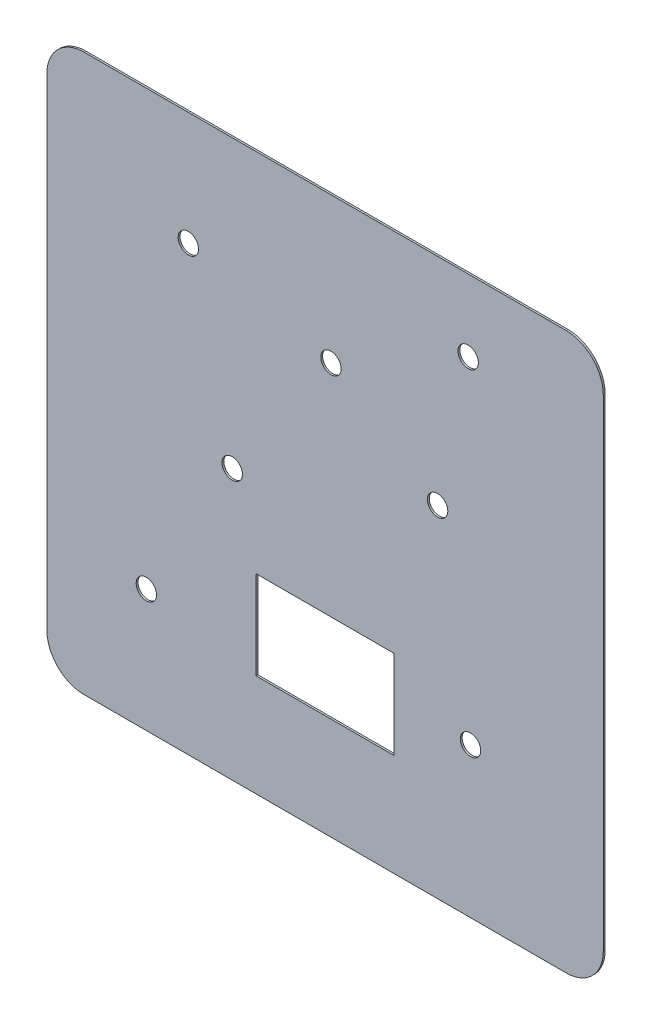
SolidWorks part; units mm, degrees
ref_plane "Piano frontale" through (0, 0, 0) normal (0, 0, 1) x (1, 0, 0)
ref_plane "Piano superiore" through (0, 0, 0) normal (0, 1, 0) x (1, 0, 0)
ref_plane "Piano destro" through (0, 0, 0) normal (1, 0, 0) x (0, 0, -1)
sketch "Schizzo1" plane through (0, 0, 0) normal (0, 0, 1) x (1, 0, 0)
  line L1 (-75, 75) -> (75, 75)
  line L2 (-75, 75) -> (-75, -75)
  line L3 (-75, -75) -> (75, -75)
  line L4 (75, 75) -> (75, -75)
  line L5 (-75, 75) -> (75, -75) construction
  line L6 (-75, -75) -> (75, 75) construction
  point P0 (0, 0)
  dimension "D1" = 150
  dimension "D2" = 150
extrude "Estrusione-Estrusione1" add sketch "Schizzo1" along normal blind 0.5
fillet "Raccordo1" radius 10 4 edges at (75, -75, 0.25) (-75, -75, 0.25) (-75, 75, 0.25) (75, 75, 0.25)
hole_wizard "Foro per Vite M5-1" positions "Schizzo3D1" profile "Schizzo2" hole size "M5" standard "ISO" end condition through all
sketch3d "Schizzo3D1"
  point P0 (-48.1797, -41.9662, 0.5)
  point P2 (-25.0341, -2.221, 0.5)
  point P4 (30.3365, 16.858, 0.5)
  point P6 (39.211, -34.6065, 0.5)
  point P8 (-36.8661, 44.4433, 0.5)
  point P10 (38.5848, 55.6384, 0.5)
  point P12 (1.5829, 35.7252, 0.5)
sketch "Schizzo2" plane through (-48.1797, -41.9662, 0.5) normal (1, 0, 0) x (0, -1, 0)
  line L0 (0, 0) -> (0, 0.5)
  line L1 (0, 0.5) -> (2.75, 0.5)
  line L2 (2.75, 0.5) -> (2.75, 0)
  line L5 (2.75, 0) -> (0, 0)
  line L11 (0, -6.35) -> (0, 107.95) construction
  dimension "Thru Hole Dia." = 5.5
  dimension "Thru Hole Depth" = 0.5
sketch "Schizzo3" plane through (0, 0, 0.5) normal (0, 0, 1) x (1, 0, 0)
  line L1 (-18.5922, -47.4299) -> (18.5922, -47.4299)
  line L2 (-18.5922, -47.4299) -> (-18.5922, -23.5807)
  line L3 (-18.5922, -23.5807) -> (18.5922, -23.5807)
  line L4 (18.5922, -47.4299) -> (18.5922, -23.5807)
  line L5 (-18.5922, -47.4299) -> (18.5922, -23.5807) construction
  line L6 (-18.5922, -23.5807) -> (18.5922, -47.4299) construction
  point P0 (0, -35.5053)
extrude "Taglio-Estrusione1" cut sketch "Schizzo3" against normal blind 1
